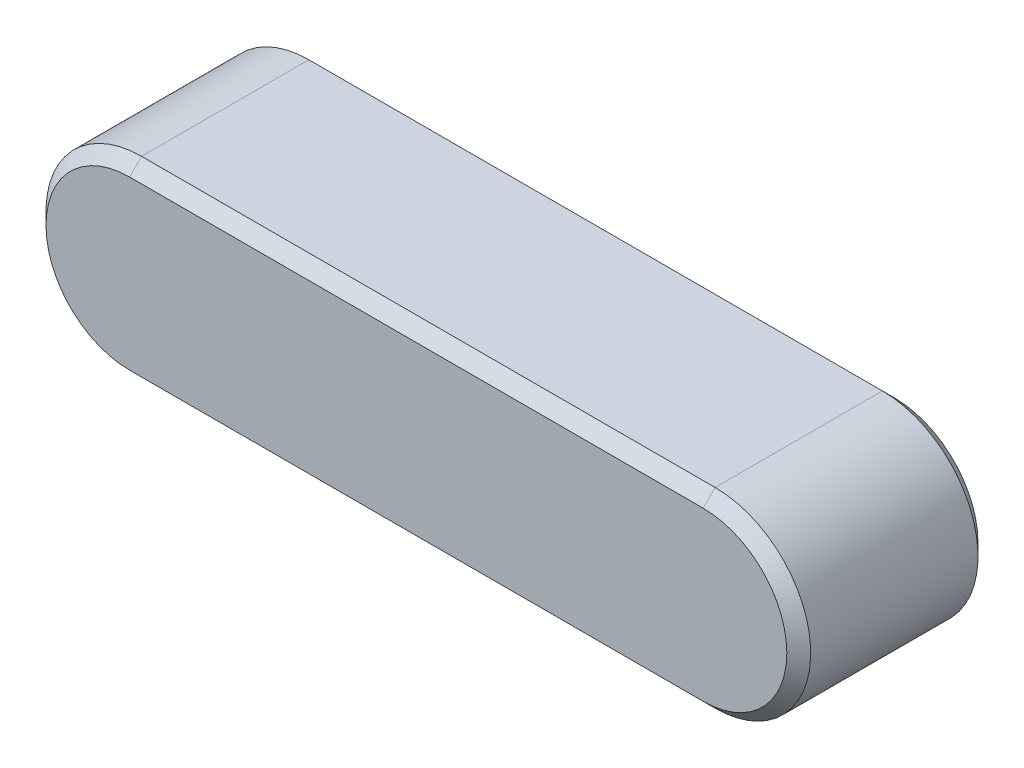
SolidWorks part; units mm, degrees
ref_plane "Front" through (0, 0, 0) normal (0, 0, 1) x (1, 0, 0)
ref_plane "Top" through (0, 0, 0) normal (0, 1, 0) x (1, 0, 0)
ref_plane "Right" through (0, 0, 0) normal (1, 0, 0) x (0, 0, -1)
sketch "Sketch1" plane through (0, 0, 0) normal (0, 0, 1) x (1, 0, 0)
  line L0 (-12, 2) -> (0, 2)
  line L1 (0, -2) -> (-12, -2)
  arc A0 (0, 2) -> (0, -2) centre (0, 0) cw
  arc A1 (-12, -2) -> (-12, 2) centre (-12, 0) cw
  dimension "L" = 16
  dimension "b" = 4
extrude "BaseKey" add sketch "Sketch1" along normal mid plane 4
sketch "Sketch2" plane through (0, 0, 0) normal (0, 0, 1) x (1, 0, 0)
  line L1 (-14, 2) -> (2, 2)
  line L2 (-14, 2) -> (-14, -2)
  line L3 (-14, -2) -> (2, -2)
  line L4 (2, 2) -> (2, -2)
  line L6 (0, -2) -> (-12, -2) construction
  line L7 (-12, 2) -> (0, 2) construction
  arc A2 (0, -2) -> (0, 2) centre (0, 0) ccw construction
  arc A3 (-12, 2) -> (-12, -2) centre (-12, 0) ccw construction
extrude "Extrude1" [suppressed] add sketch "Sketch2" along normal mid plane 4
sketch "Sketch3" plane through (0, 0, 0) normal (0, 0, 1) x (1, 0, 0)
  line L0 (2, 2) -> (-12, 2)
  line L1 (-12, -2) -> (2, -2)
  line L2 (2, -2) -> (2, 2)
  line L5 (-12, 2) -> (0, 2) construction
  arc A0 (-12, 2) -> (-12, -2) centre (-12, 0) ccw
  arc A1 (0, -2) -> (0, 2) centre (0, 0) ccw construction
  arc A4 (-12, 2) -> (-12, -2) centre (-12, 0) ccw construction
extrude "Extrude2" [suppressed] add sketch "Sketch3" along normal mid plane 4
chamfer "Chamfer1" distance 0.25 angle 45 8 edges at (2, 0, -2) (-6, -2, -2) (-14, 0, -2) (-6, 2, -2) (-14, 0, 2) (-6, -2, 2) (2, 0, 2) (-6, 2, 2)
equation "\"D1@Extrude1\"=\"h@BaseKey\""
equation "\"D1@Extrude2\"=\"h@BaseKey\""
